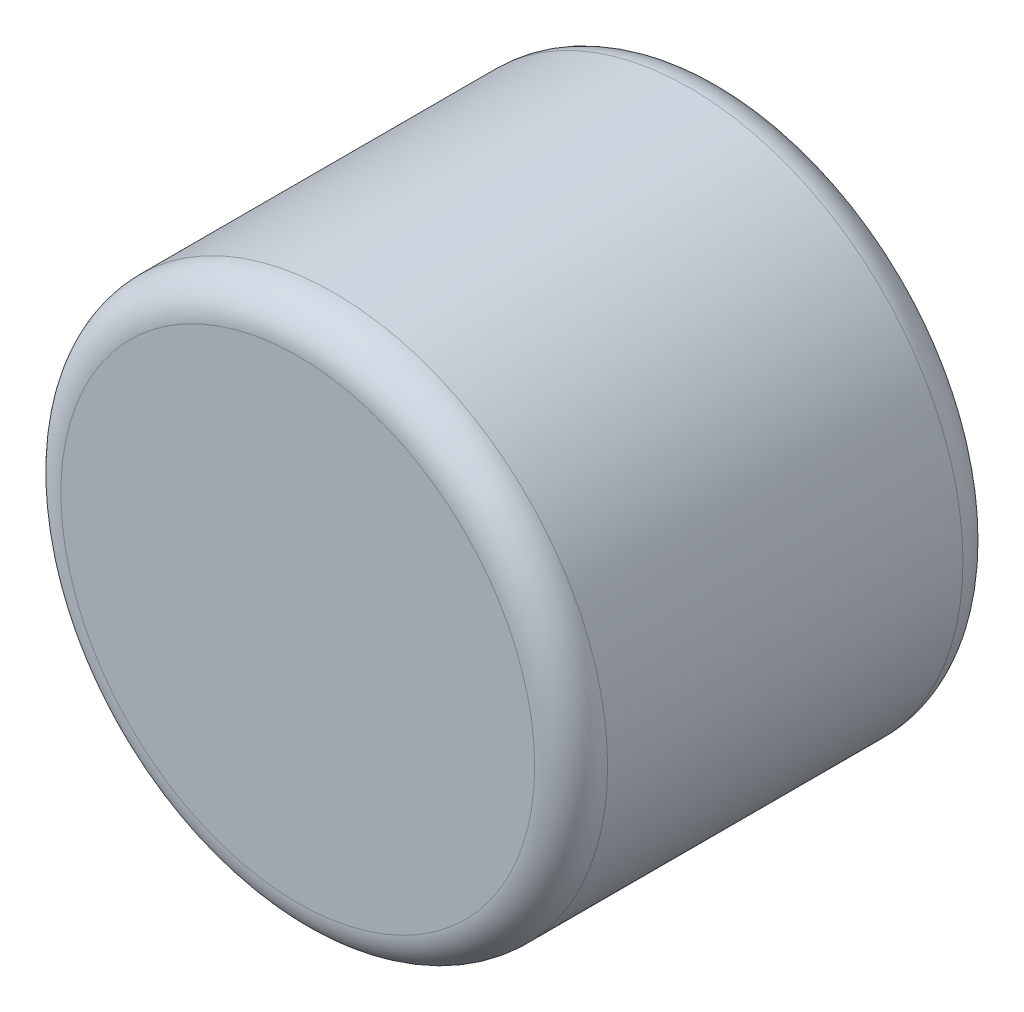
SolidWorks part; units mm, degrees
ref_plane "Ön Düzlem" through (0, 0, 0) normal (0, 0, 1) x (1, 0, 0)
ref_plane "Üst Düzlem" through (0, 0, 0) normal (0, 1, 0) x (1, 0, 0)
ref_plane "Sağ Düzlem" through (0, 0, 0) normal (1, 0, 0) x (0, 0, -1)
sketch "Çizim1" plane through (0, 0, 0) normal (0, 0, 1) x (1, 0, 0)
  circle A0 centre (0, 0) radius 7.5
  dimension "D1" = 15
extrude "Yükseklik-Ekstrüzyon1" add sketch "Çizim1" along normal blind 11.75
ref_plane "Düzlem1" through (0, 0, 9.75) normal (0, 0, -1) x (-1, 0, 0)
sketch "Çizim2" plane through (0, 0, 9.75) normal (0, 0, 1) x (1, 0, 0)
  line L0 (-2.6557, -1.5) -> (2.6557, -1.5)
  arc A0 (2.6557, -1.5) -> (-2.6557, -1.5) centre (0, 0) ccw
  dimension "D1" = 6.1
  dimension "D2" = 4.55
extrude "Kes-Ekstrüzyon1" cut sketch "Çizim2" against normal blind 7
fillet "Radyus1" radius 1 2 edges at (7.5, 0, 11.75) (7.5, 0, 0)
sketch "Çizim3" plane through (0, 0, 0) normal (0, 0, -1) x (-1, 0, 0)
  circle A0 centre (0, 0) radius 3.05
  dimension "D1" = 6.1
extrude "Kes-Ekstrüzyon2" cut sketch "Çizim3" against normal blind 2.75
